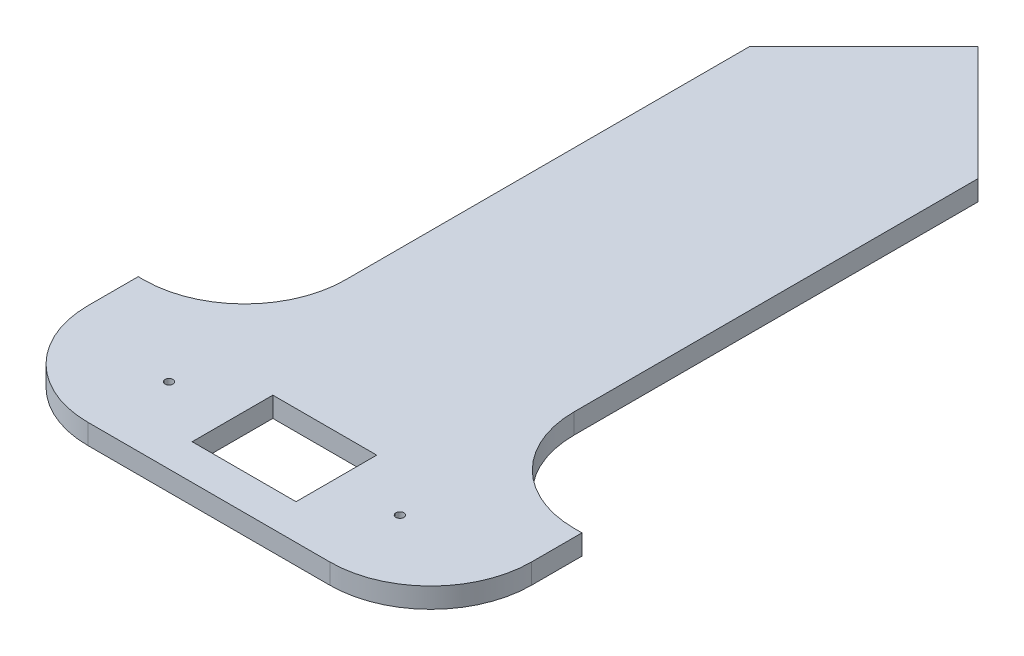
SolidWorks part; units mm, degrees
ref_plane "Front Plane" through (0, 0, 0) normal (0, 0, 1) x (1, 0, 0)
ref_plane "Top Plane" through (0, 0, 0) normal (0, 1, 0) x (1, 0, 0)
ref_plane "Right Plane" through (0, 0, 0) normal (1, 0, 0) x (0, 0, -1)
sketch "Sketch2" plane through (0, 0, 0) normal (0, 1, 0) x (1, 0, 0)
  line L1 (-22, 7.5) -> (22, 7.5)
  line L2 (-22, 7.5) -> (-22, -7.5)
  line L3 (-22, -7.5) -> (22, -7.5)
  line L4 (22, 7.5) -> (22, -7.5)
  line L5 (-22, 7.5) -> (22, -7.5) construction
  line L6 (-22, -7.5) -> (22, 7.5) construction
  point P0 (0, 0)
  dimension "D1" = 44
  dimension "D2" = 15
extrude "Boss-Extrude1" add sketch "Sketch2" along normal blind 2
sketch "Sketch3" plane through (0, 2, 0) normal (0, 1, 0) x (1, 0, 0)
  line L1 (-5.15, 4) -> (5.15, 4)
  line L2 (-5.15, 4) -> (-5.15, -4)
  line L3 (-5.15, -4) -> (5.15, -4)
  line L4 (5.15, 4) -> (5.15, -4)
  line L5 (-5.15, 4) -> (5.15, -4) construction
  line L6 (-5.15, -4) -> (5.15, 4) construction
  point P0 (0, 0)
  dimension "D1" = 8
  dimension "D2" = 10.3
extrude "Cut-Extrude1" cut sketch "Sketch3" against normal blind 2
sketch "Sketch4" plane through (0, 2, 0) normal (0, 1, 0) x (1, 0, 0)
  line L0 (0, 0) -> (-16.7619, 0) construction
  line L1 (-16.7619, 0) -> (16.9441, 0) construction
  line L2 (-5.15, 4) -> (-5.15, -4) construction
  circle A0 centre (-11.45, 0) radius 0.4
  dimension "D1" = 0.8
  dimension "D2" = 6.3
sketch "Sketch5" plane through (0, 2, 0) normal (0, 1, 0) x (1, 0, 0)
  circle A0 centre (-11.45, 0) radius 0.4
extrude "Cut-Extrude2" cut sketch "Sketch5" against normal blind 2
mirror "Mirror1" about plane through (0, 0, 0) normal (1, 0, 0) of "Cut-Extrude2"
sketch "Sketch6" plane through (0, 2, 0) normal (0, 1, 0) x (1, 0, 0)
  line L0 (22, 7.5) -> (-22, 7.5) construction
  line L1 (-11.45, 7.5) -> (11.2166, 7.5)
  line L2 (-11.45, 7.5) -> (-11.45, 68.885)
  line L3 (-11.45, 68.885) -> (11.2166, 68.885)
  line L4 (11.2166, 7.5) -> (11.2166, 68.885)
extrude "Boss-Extrude3" add sketch "Sketch6" against normal blind 2
fillet "Fillet1" radius 10 2 edges at (11.2166, 1, -7.5) (-11.45, 1, -7.5)
sketch "Sketch8" plane through (0, 2, 0) normal (0, 1, 0) x (1, 0, 0)
  line L0 (-0.1167, 68.885) -> (-11.45, 57.5517)
  line L1 (11.2166, 68.885) -> (-11.45, 68.885) construction
  line L2 (-11.45, 68.885) -> (-11.45, 17.5) construction
extrude "Cut-Extrude3" cut sketch "Sketch8" against normal blind 2 and the other way through all flip side to cut
sketch "Sketch9" plane through (0, 2, 0) normal (0, 1, 0) x (1, 0, 0)
  line L0 (-0.1167, 68.885) -> (11.2166, 57.5517)
  line L1 (11.2166, 17.5) -> (11.2166, 68.885) construction
extrude "Cut-Extrude4" cut sketch "Sketch9" against normal blind 2 and the other way through all
fillet "Fillet2" radius 10 2 edges at (22, 1, 7.5) (-22, 1, 7.5)
